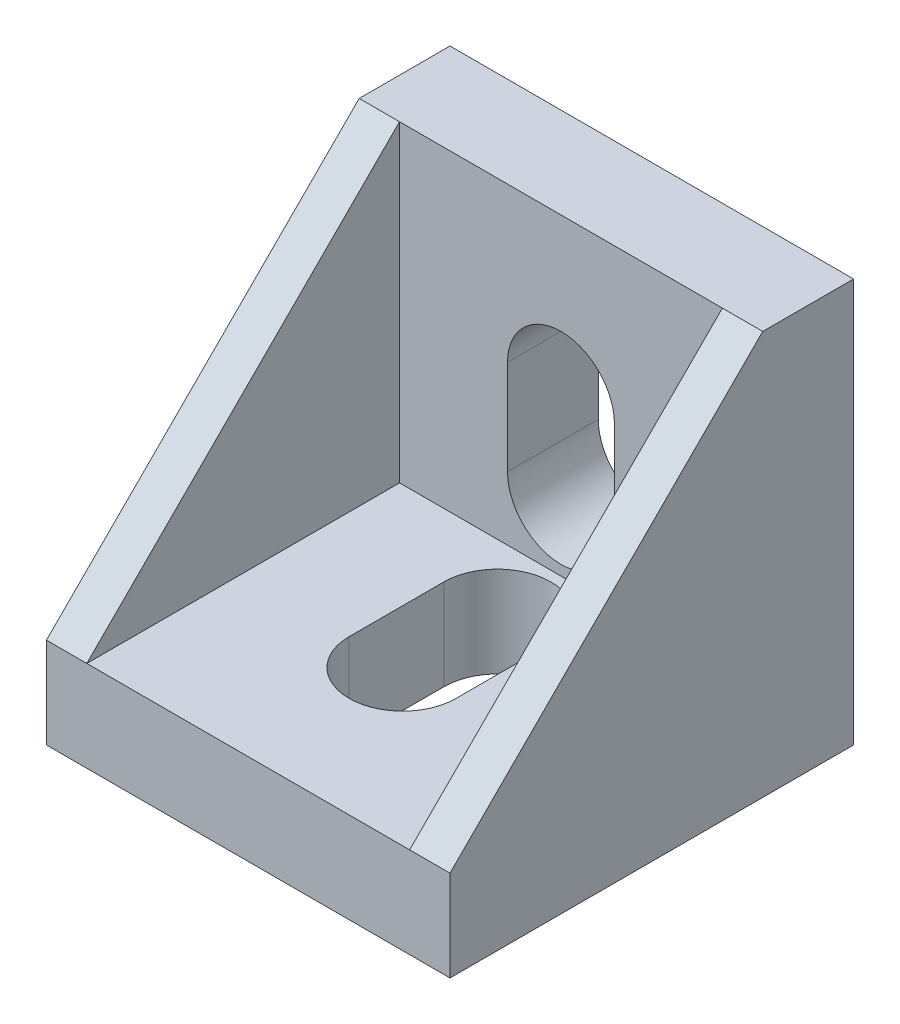
SolidWorks part; units mm, degrees
ref_plane "Front Plane" through (0, 0, 0) normal (0, 0, 1) x (1, 0, 0)
ref_plane "Top Plane" through (0, 0, 0) normal (0, 1, 0) x (1, 0, 0)
ref_plane "Right Plane" through (0, 0, 0) normal (1, 0, 0) x (0, 0, -1)
sketch "Sketch1" plane through (0, 0, 0) normal (0, 0, 1) x (1, 0, 0)
  line L0 (0, 2.823) -> (20, 2.823)
  line L1 (0, -7.177) -> (20, -7.177)
  line L2 (0, -7.177) -> (0, 12.823)
  line L3 (0, 12.823) -> (20, 12.823)
  line L4 (20, -7.177) -> (20, 12.823)
  line L11 (7.35, 5.173) -> (7.35, 0.473)
  line L12 (12.65, 5.173) -> (12.65, 0.473)
  arc A0 (7.35, 0.473) -> (12.65, 0.473) centre (10, 0.473) ccw
  arc A1 (7.35, 5.173) -> (12.65, 5.173) centre (10, 5.173) cw
  point P7 (10, 7.823)
  point P8 (10, -2.177)
  point P15 (0, 0)
  point P20 (10, 2.823)
  point P21 (0, 0)
  dimension "D4" = 5.3
  dimension "D7" = 0.473
  dimension "D1" = 20
  dimension "D2" = 20
  dimension "D5" = 2.823
  dimension "D6" = 15
  dimension "D3" = 5
extrude "Boss-Extrude1" add sketch "Sketch1" along normal blind 4.5 contours A0 L0 L4 L3 L2 | A0 L0 L2 L1 L4
sketch "Sketch2" plane through (0, -7.177, 0) normal (0, -1, 0) x (1, 0, 0)
  line L1 (0, 0) -> (20, 0)
  line L2 (0, 0) -> (0, 20)
  line L3 (0, 20) -> (20, 20)
  line L4 (20, 0) -> (20, 20)
  line L5 (20, 10) -> (0, 10)
  line L8 (12.65, 7.65) -> (12.65, 12.35)
  line L9 (7.35, 7.65) -> (7.35, 12.35)
  arc A0 (7.35, 7.65) -> (12.65, 7.65) centre (10, 7.65) ccw
  arc A1 (12.65, 12.35) -> (7.35, 12.35) centre (10, 12.35) ccw
  point P5 (10, 5)
  point P12 (10, 10)
  point P14 (10, 15)
  dimension "D5" = 5.3
  dimension "D6" = 5.3
  dimension "D4" = 15
  dimension "D1" = 20
  dimension "D2" = 20
  dimension "D3" = 5
extrude "Boss-Extrude2" add sketch "Sketch2" against normal blind 4.5
sketch "Sketch4" plane through (20, 0, 0) normal (1, 0, 0) x (0, 0, -1)
  line L0 (-20, -2.677) -> (-4.5, 12.823)
  line L1 (-20, -2.677) -> (-4.5, -2.677)
  line L2 (-4.5, -2.677) -> (-4.5, 12.823)
extrude "Boss-Extrude3" add sketch "Sketch4" against normal blind 2
ref_plane "Plane1" through (10, 0, 0) normal (1, 0, 0) x (0, 0, -1)
mirror "Mirror1" about plane through (10, 0, 0) normal (1, 0, 0) of "Boss-Extrude3"
